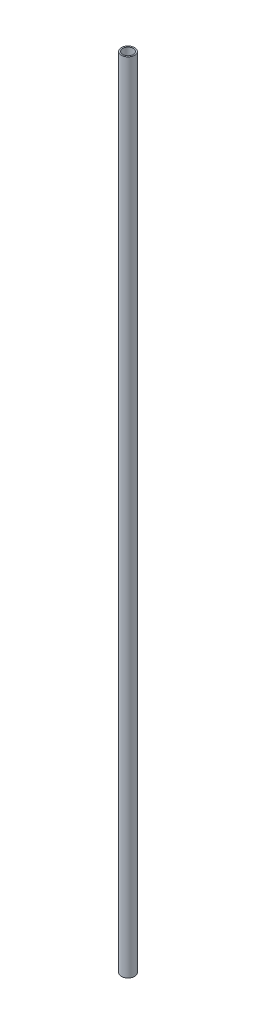
SolidWorks part; units mm, degrees
material "Thornel Mat VMA"
ref_plane "Front Plane" through (0, 0, 0) normal (0, 0, 1) x (1, 0, 0)
ref_plane "Top Plane" through (0, 0, 0) normal (0, 1, 0) x (1, 0, 0)
ref_plane "Right Plane" through (0, 0, 0) normal (1, 0, 0) x (0, 0, -1)
sketch "Sketch1" plane through (0, 0, 0) normal (0, 1, 0) x (1, 0, 0)
  circle A0 centre (0, 0) radius 4
  circle A1 centre (0, 0) radius 5
  dimension "D1" = 10
  dimension "D2" = 8
extrude "Boss-Extrude1" add sketch "Sketch1" along normal blind 600
